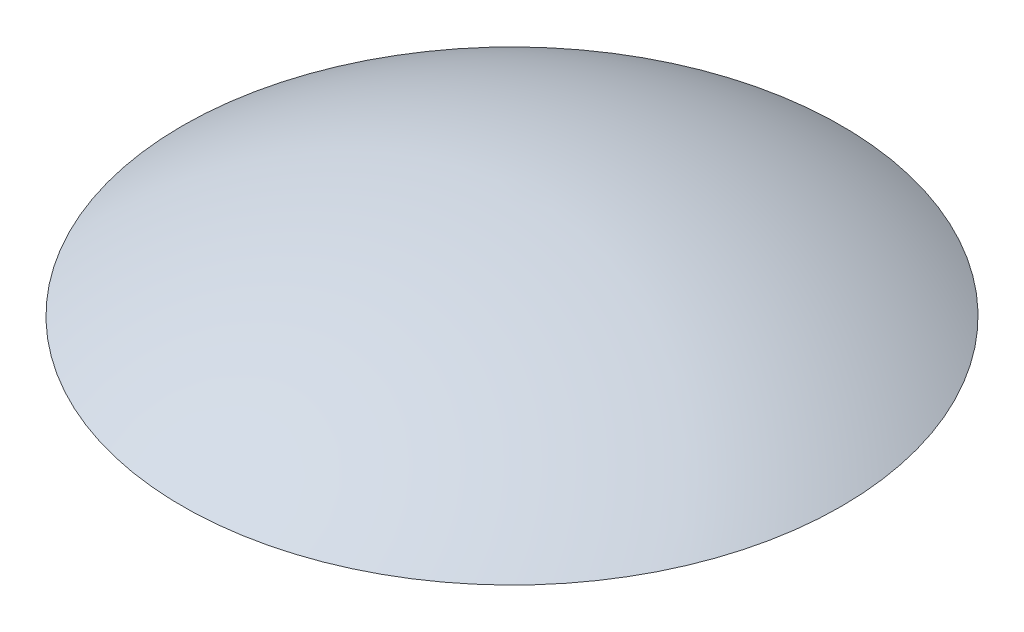
SolidWorks part; units mm, degrees
ref_plane "Front Plane" through (0, 0, 0) normal (0, 0, 1) x (1, 0, 0)
ref_plane "Top Plane" through (0, 0, 0) normal (0, 1, 0) x (1, 0, 0)
ref_plane "Right Plane" through (0, 0, 0) normal (1, 0, 0) x (0, 0, -1)
sketch "Sketch1" plane through (0, 0, 0) normal (0, 0, 1) x (1, 0, 0)
  line L0 (-101.6514, 28.8498) -> (-101.4014, 28.8498)
  line L1 (-101.6514, 28.8498) -> (-61.6793, 55.2066) construction
  line L2 (-101.4014, 28.8498) -> (-101.4014, 28.9248)
  arc A0 (-101.4014, 28.9248) -> (-101.6514, 28.8498) centre (-101.4014, 28.4707) ccw
  dimension "D1" = 33.4
  dimension "D2" = 0.25
revolve "Revolve4" add sketch "Sketch1" angle 360 about L2
